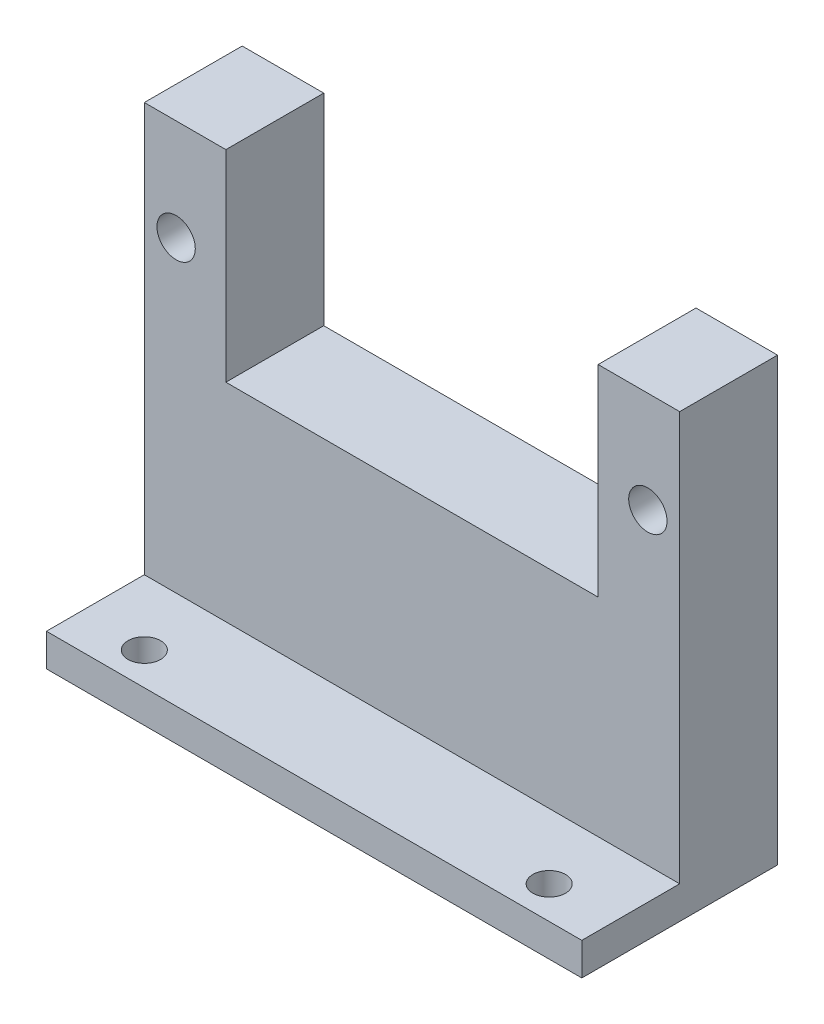
SolidWorks part; units mm, degrees
ref_plane "Front Plane" through (0, 0, 0) normal (0, 0, 1) x (1, 0, 0)
ref_plane "Top Plane" through (0, 0, 0) normal (0, 1, 0) x (1, 0, 0)
ref_plane "Right Plane" through (0, 0, 0) normal (1, 0, 0) x (0, 0, -1)
ref_plane "Plane1" through (0, 0, 0) normal (0, 0, -1) x (-1, 0, 0)
sketch "Sketch1" plane through (0, 0, 0) normal (0, 0, -1) x (-1, 0, 0)
  line L0 (-32.82, 0) -> (0, 0)
  line L1 (0, 0) -> (0, 27.07)
  line L2 (0, 27.07) -> (-32.82, 27.07)
  line L3 (-32.82, 27.07) -> (-32.82, 0)
extrude "Boss-Extrude1" add sketch "Sketch1" against normal blind 12
sketch "Sketch2" plane through (0, 0, 0) normal (-1, 0, 0) x (0, 0, 1)
  line L0 (6, 27.07) -> (6, 2)
  line L1 (6, 2) -> (12, 2)
  line L2 (12, 2) -> (12, 27.07)
  line L3 (12, 27.07) -> (6, 27.07)
extrude "Cut-Extrude1" cut sketch "Sketch2" against normal through all
sketch "Sketch3" plane through (0, 0, 0) normal (0, 0, -1) x (-1, 0, 0)
  line L0 (-5, 27.07) -> (-27.82, 27.07)
  line L1 (-27.82, 27.07) -> (-27.82, 14.72)
  line L2 (-27.82, 14.72) -> (-5, 14.72)
  line L3 (-5, 14.72) -> (-5, 27.07)
extrude "Cut-Extrude2" cut sketch "Sketch3" against normal through all
hole_wizard "Ø2.35 (2.35) Diameter Hole1" positions "Sketch5" profile "Sketch4" hole size "Ø2.35" standard "ANSI Metric"
sketch "Sketch5" plane through (0, 0, 6) normal (0, 0, 1) x (1, 0, 0)
  point P0 (1.95, 20.87)
  point P1 (30.87, 20.87)
sketch "Sketch4" plane through (1.95, 20.87, 6) normal (1, 0, 0) x (0, -1, 0)
  line L0 (0, 0) -> (0, 6)
  line L1 (0, 6) -> (1.175, 6)
  line L2 (1.175, 6) -> (1.175, 0)
  line L5 (1.175, 0) -> (0, 0)
  line L11 (0, -6.35) -> (0, 107.95) construction
  dimension "Thru Hole Dia." = 2.35
  dimension "Thru Hole Depth" = 6
hole_wizard "Ø2.0 (2) Diameter Hole1" positions "Sketch7" profile "Sketch6" hole size "Ø2.0" standard "ANSI Metric"
sketch "Sketch7" plane through (0, 2, 0) normal (0, 1, 0) x (1, 0, 0)
  point P0 (28.82, -10)
  point P1 (4, -10)
sketch "Sketch6" plane through (28.82, 2, 10) normal (1, 0, 0) x (0, 0, 1)
  line L0 (0, 0) -> (0, 2)
  line L1 (0, 2) -> (1, 2)
  line L2 (1, 2) -> (1, 0)
  line L5 (1, 0) -> (0, 0)
  line L11 (0, -6.35) -> (0, 107.95) construction
  dimension "Thru Hole Dia." = 2
  dimension "Thru Hole Depth" = 2
